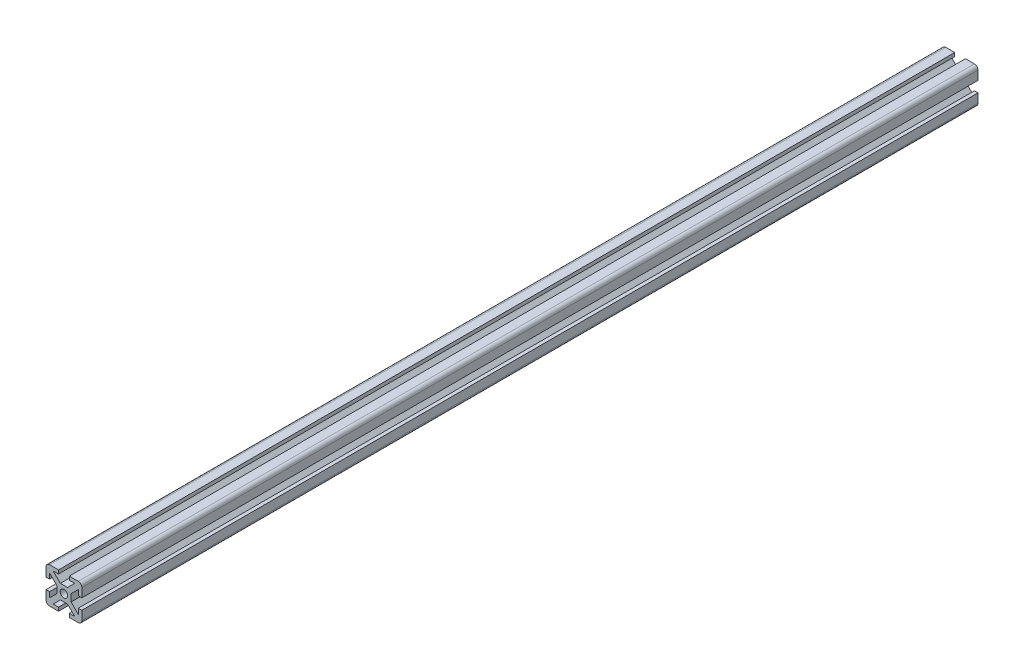
SolidWorks part; units mm, degrees
ref_plane "Front Plane" through (0, 0, 0) normal (0, 0, 1) x (1, 0, 0)
ref_plane "Top Plane" through (0, 0, 0) normal (0, 1, 0) x (1, 0, 0)
ref_plane "Right Plane" through (0, 0, 0) normal (1, 0, 0) x (0, 0, -1)
sketch "Sketch1" plane through (0, 0, 0) normal (0, 0, 1) x (1, 0, 0)
  line L0 (-16.7514, 0) -> (23.2798, 0) construction
  line L1 (-2, -4) -> (2, -4)
  line L2 (-4, -2) -> (-4, 2)
  line L3 (-2, 4) -> (2, 4)
  line L4 (4, -2) -> (4, 2)
  line L5 (-10, 8) -> (-10, 3)
  line L11 (0, 0) -> (-10, 10) construction
  line L12 (0, 0) -> (10, 10) construction
  line L17 (-6, 8) -> (-2, 4)
  line L18 (-3, 8) -> (-6, 8)
  line L19 (0, 14.6931) -> (0, -18.977) construction
  line L20 (8, 10) -> (3, 10)
  line L21 (3, 10) -> (3, 8)
  line L22 (3, 8) -> (6, 8)
  line L23 (6, 8) -> (2, 4)
  line L24 (-3, 10) -> (-3, 8)
  line L25 (-8, 10) -> (-3, 10)
  line L26 (0, 0) -> (10, -10) construction
  line L27 (8, -10) -> (3, -10)
  line L28 (3, -10) -> (3, -8)
  line L29 (3, -8) -> (6, -8)
  line L30 (6, -8) -> (2, -4)
  line L31 (-6, -8) -> (-2, -4)
  line L32 (-3, -10) -> (-3, -8)
  line L33 (-3, -8) -> (-6, -8)
  line L34 (0, 0) -> (-10, -10) construction
  line L35 (-8, -10) -> (-3, -10)
  line L36 (-10, 3) -> (-8, 3)
  line L37 (-8, 3) -> (-8, 6)
  line L38 (-8, 6) -> (-4, 2)
  line L39 (-8, -6) -> (-4, -2)
  line L40 (-8, -3) -> (-8, -6)
  line L41 (-10, -3) -> (-8, -3)
  line L42 (-10, -8) -> (-10, -3)
  line L43 (8, -6) -> (4, -2)
  line L44 (8, -3) -> (8, -6)
  line L45 (10, -3) -> (8, -3)
  line L46 (10, -8) -> (10, -3)
  line L47 (8, 6) -> (4, 2)
  line L48 (8, 3) -> (8, 6)
  line L49 (10, 3) -> (8, 3)
  line L50 (10, 8) -> (10, 3)
  circle A0 centre (0, 0) radius 2.1
  arc A1 (-10, -8) -> (-8, -10) centre (-8, -8) ccw
  arc A2 (10, -8) -> (8, -10) centre (8, -8) cw
  arc A3 (8, 10) -> (10, 8) centre (8, 8) cw
  arc A4 (-10, 8) -> (-8, 10) centre (-8, 8) cw
  point P8 (-8, 6.7277)
  dimension "D1" = 4.2
  dimension "D9" = 2
  dimension "D2" = 4
  dimension "D3" = 4
  dimension "D4" = 10
  dimension "D5" = 45
  dimension "D6" = 3
  dimension "D7" = 6
  dimension "D8" = 2
extrude "Boss-Extrude1" add sketch "Sketch1" along normal blind 500
